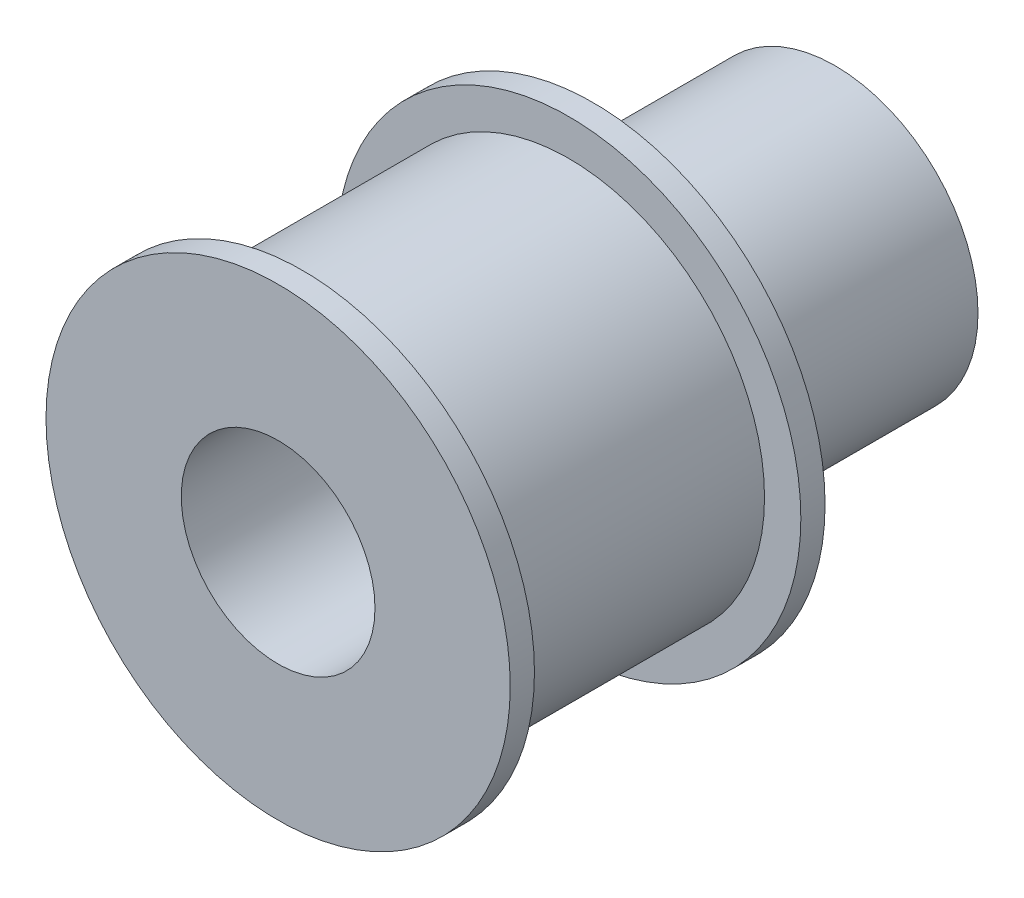
SolidWorks part; units mm, degrees
ref_plane "Front Plane" through (0, 0, 0) normal (0, 0, 1) x (1, 0, 0)
ref_plane "Top Plane" through (0, 0, 0) normal (0, 1, 0) x (1, 0, 0)
ref_plane "Right Plane" through (0, 0, 0) normal (1, 0, 0) x (0, 0, -1)
sketch "Sketch1" plane through (0, 0, 0) normal (0, 1, 0) x (1, 0, 0)
  line L0 (0, 0) -> (0, 161.9291) construction
  line L1 (0, 23) -> (-5.9, 23)
  line L2 (-5.9, 23) -> (-5.9, 13)
  line L3 (-5.9, 13) -> (-9.5851, 13)
  line L4 (-9.5851, 13) -> (-9.5851, 12)
  line L5 (-9.5851, 12) -> (-8.0851, 12)
  line L6 (-8.0851, 12) -> (-8.0851, 1)
  line L7 (-8.0851, 1) -> (-9.5851, 1)
  line L8 (-9.5851, 1) -> (-9.5851, 0)
  line L9 (-9.5851, 0) -> (0, 0)
  line L10 (0, 0) -> (0, 23)
  line L11 (-9.5851, 12) -> (-9.5851, 1) construction
  dimension "D1" = 8.0851
  dimension "D2" = 1.5
  dimension "D3" = 11
  dimension "D4" = 1
  dimension "D5" = 1
  dimension "D6" = 10
  dimension "D7" = 5.9
revolve "Revolve1" add sketch "Sketch1" angle 360 about L10
sketch "Sketch2" plane through (0, 0, 0) normal (0, 0, 1) x (1, 0, 0)
  circle A0 centre (0, 0) radius 4
  circle A1 centre (0, 0) radius 9.5851 construction
  dimension "D1" = 8
extrude "Cut-Extrude1" cut sketch "Sketch2" against normal through all
sketch "Sketch3" plane through (0, 0, 0) normal (0, 1, 0) x (1, 0, 0)
  line L0 (0, 23) -> (0, 13) construction
  line L1 (5.9, 23) -> (-5.9, 23) construction
  circle A0 centre (0, 18) radius 1.5
  dimension "D1" = 5
  dimension "D2" = 3
extrude "Cut-Extrude2" cut sketch "Sketch3" against normal through all
sketch "Sketch4" plane through (0, 0, 0) normal (1, 0, 0) x (0, 0, -1)
  line L0 (23, 0) -> (13, 0) construction
  line L1 (23, -5.9) -> (23, 5.9) construction
  circle A0 centre (18, 0) radius 1.5
  dimension "D1" = 5
  dimension "D2" = 3
extrude "Cut-Extrude3" cut sketch "Sketch4" against normal through all
ref_plane "Plane1" through (0, 0, -6.5) normal (0, 0, 1) x (1, 0, 0)
equation "\"teeth\"= 10"
equation "\"pitch\"= .2in"
equation "\"pitch diameter\"= \"teeth\" * \"pitch\" / pi"
equation "\"D1@Sketch1\"=\"pitch diameter\"/2"
